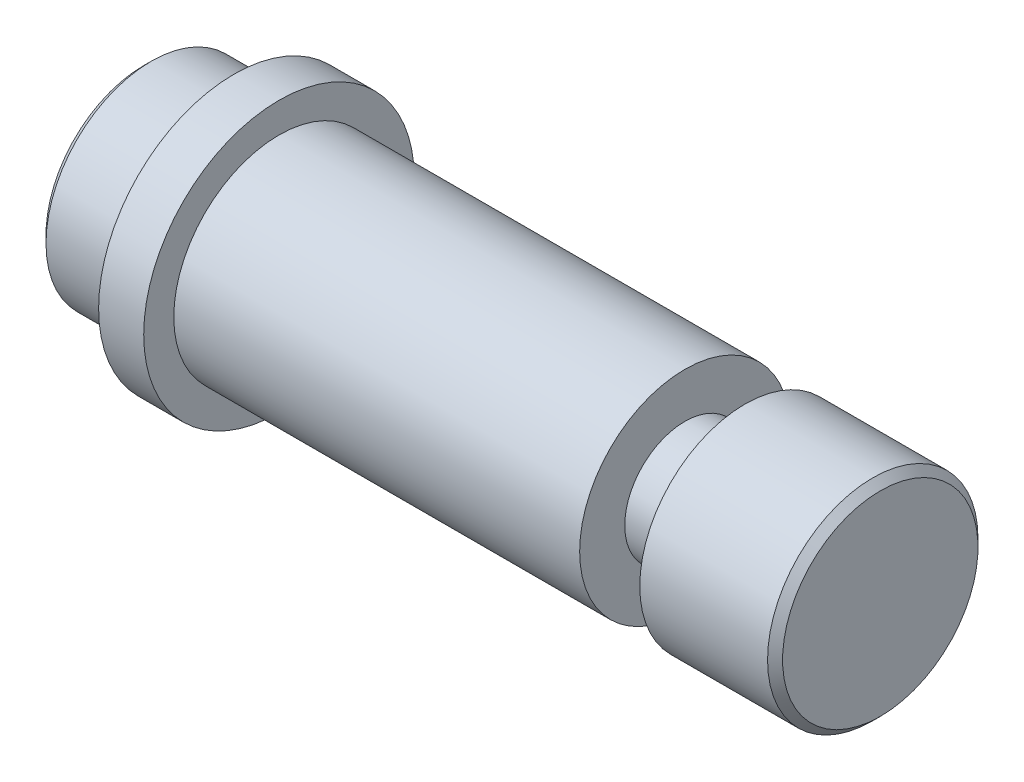
SolidWorks part; units mm, degrees
ref_plane "Front" through (0, 0, 0) normal (0, 0, 1) x (1, 0, 0)
ref_plane "Top" through (0, 0, 0) normal (0, 1, 0) x (1, 0, 0)
ref_plane "Right" through (0, 0, 0) normal (1, 0, 0) x (0, 0, -1)
sketch "草图1" plane through (0, 0, 0) normal (0, 0, 1) x (1, 0, 0)
  line L0 (-18.3988, 0) -> (-18.3988, 7)
  line L1 (-18.3988, 7) -> (-12.3988, 7)
  line L2 (-12.3988, 7) -> (-12.3988, 9)
  line L3 (-12.3988, 9) -> (-9.3988, 9)
  line L4 (-9.3988, 9) -> (-9.3988, 7)
  line L5 (-9.3988, 7) -> (17.6012, 7)
  line L6 (17.6012, 7) -> (17.6012, 4)
  line L7 (17.6012, 4) -> (21.6012, 4)
  line L8 (21.6012, 4) -> (21.6012, 7)
  line L9 (21.6012, 7) -> (30.6012, 7)
  line L10 (30.6012, 7) -> (30.6012, 0)
  line L11 (30.6012, 0) -> (-18.3988, 0)
  dimension "D1" = 7
  dimension "D2" = 6
  dimension "D3" = 3
  dimension "D4" = 27
  dimension "D5" = 4
  dimension "D6" = 9
  dimension "D7" = 7
  dimension "D8" = 9
  dimension "D9" = 4
revolve "旋转1" add sketch "草图1" angle 360 about L11
chamfer "倒角1" distance 0.5 angle 45 2 edges at (30.6012, 7, 0) (-18.3988, 7, 0)
